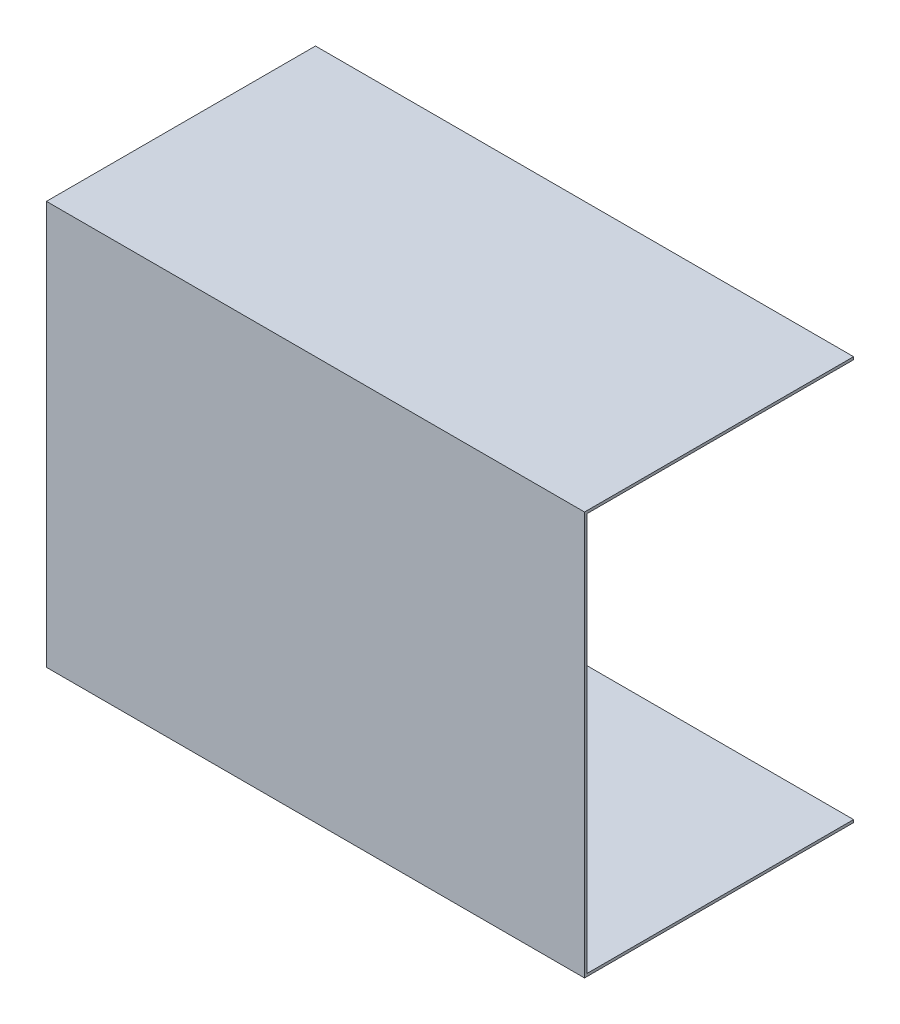
SolidWorks part; units mm, degrees
ref_plane "前视基准面" through (0, 0, 0) normal (0, 0, 1) x (1, 0, 0)
ref_plane "上视基准面" through (0, 0, 0) normal (0, 1, 0) x (1, 0, 0)
ref_plane "右视基准面" through (0, 0, 0) normal (1, 0, 0) x (0, 0, -1)
other "Configuration Table"
sketch "草图1" plane through (0, 0, 0) normal (0, 1, 0) x (1, 0, 0)
  line L1 (-1000, 500) -> (1000, 500)
  line L2 (-1000, 500) -> (-1000, -500)
  line L3 (-1000, -500) -> (1000, -500)
  line L4 (1000, 500) -> (1000, -500)
  line L5 (-1000, 500) -> (1000, -500) construction
  line L6 (-1000, -500) -> (1000, 500) construction
  point P0 (0, 0)
  dimension "D1" = 2000
  dimension "D2" = 1000
extrude "凸台-拉伸1" add sketch "草图1" along normal blind 1500
shell "抽壳1" thickness 10
